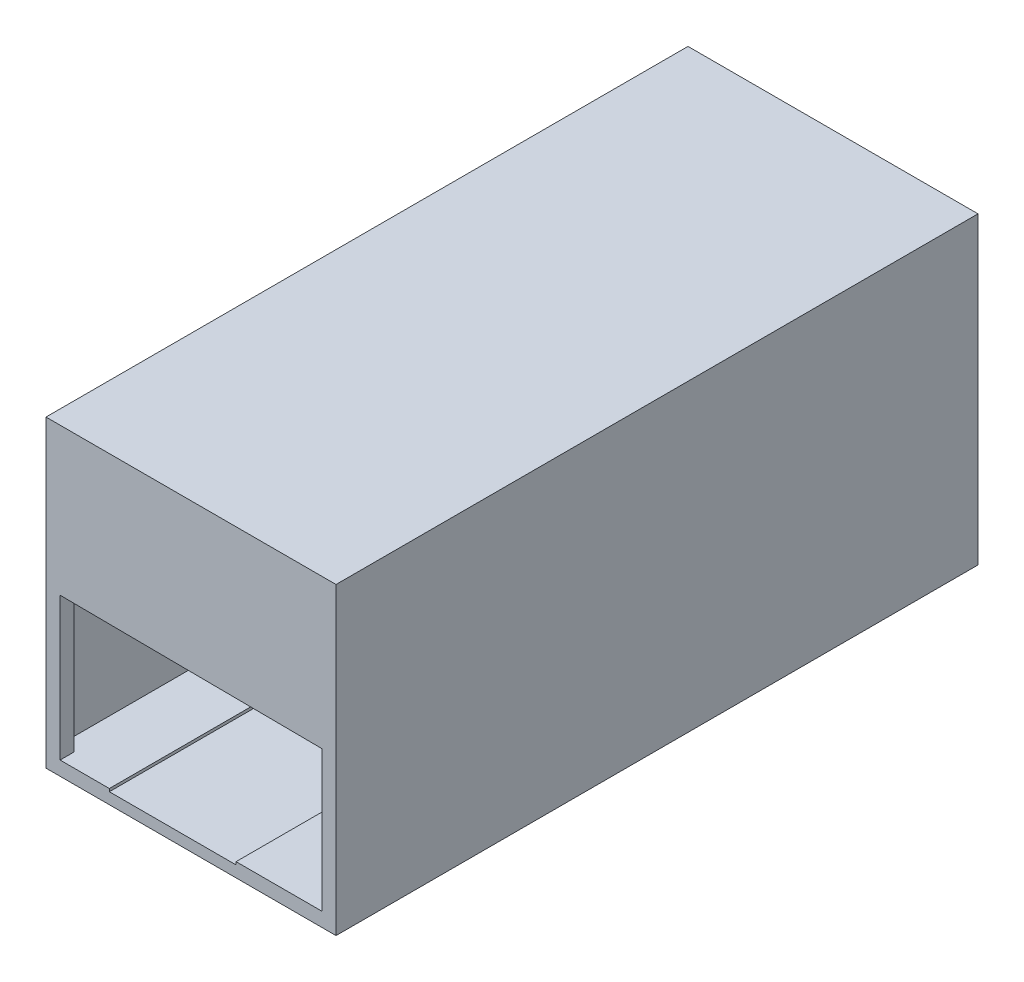
SolidWorks part; units mm, degrees
ref_plane "前视基准面" through (0, 0, 0) normal (0, 0, 1) x (1, 0, 0)
ref_plane "上视基准面" through (0, 0, 0) normal (0, 1, 0) x (1, 0, 0)
ref_plane "右视基准面" through (0, 0, 0) normal (1, 0, 0) x (0, 0, -1)
sketch "草图1" plane through (0, 0, 0) normal (0, 0, 1) x (1, 0, 0)
  line L1 (-51.5, -54) -> (51.5, -54)
  line L2 (-51.5, -54) -> (-51.5, 54)
  line L3 (-51.5, 54) -> (51.5, 54)
  line L4 (51.5, -54) -> (51.5, 54)
  line L5 (-51.5, -54) -> (51.5, 54) construction
  line L6 (-51.5, 54) -> (51.5, -54) construction
  point P0 (0, 0)
  dimension "D1" = 103
  dimension "D2" = 108
extrude "凸台-拉伸1" add sketch "草图1" against normal blind 228
sketch "草图2" plane through (0, 0, 0) normal (0, 0, 1) x (1, 0, 0)
  line L5 (-51.3, -49) -> (51.3, -49)
  line L6 (51.3, -49) -> (51.3, 49)
  line L9 (-0.804, 49) -> (51.3, 49)
  line L10 (-0.804, 49) -> (-51.3, 49)
  line L11 (-51.3, 49) -> (-51.3, -49)
extrude "切除-拉伸1" cut sketch "草图2" against normal offset from surface (218 mm away) 5 from offset 5 up to face at (0, 0, -228) offset against normal yes
sketch "草图3" plane through (0, 0, 0) normal (0, 0, 1) x (1, 0, 0)
  line L0 (51.5, -54) -> (21.4, -54) construction
  line L1 (-51.5, -54) -> (51.5, -54) construction
  line L2 (21.4, -54) -> (21.4, -24.37) construction
  circle A0 centre (21.4, -24.37) radius 8
  dimension "D3" = 16
  dimension "D1" = 30.1
  dimension "D2" = 29.63
extrude "切除-拉伸2" cut sketch "草图3" against normal blind 363
sketch "草图4" plane through (-51.5, 0, 0) normal (-1, 0, 0) x (0, 0, 1)
  line L0 (-114, 54) -> (-114, 5.82) construction
  line L1 (-228, 54) -> (0, 54) construction
  circle A0 centre (-114, 5.82) radius 23.5
  dimension "D2" = 47
  dimension "D1" = 48.18
extrude "切除-拉伸3" cut sketch "草图4" against normal up to next
sketch "草图8" plane through (0, 0, 0) normal (0, 0, 1) x (1, 0, 0)
  line L2 (0, -49) -> (46.5, -49)
  line L3 (-46.5, 1.7085) -> (-46.5, -49)
  line L7 (46.5, -49) -> (46.5, 1)
  line L8 (-46.5, -49) -> (0, -49)
  line L9 (-46.5, 1.7085) -> (46.5, 1)
  dimension "D4" = 50
extrude "切除-拉伸5" cut sketch "草图8" against normal blind 444
sketch "草图9" plane through (0, -49, 0) normal (0, 1, 0) x (1, 0, 0)
  line L1 (51.5, 0) -> (-51.5, 0) construction
  line L10 (51.5, 228) -> (-51.5, 228) construction
  line L11 (-29, 228) -> (11, 228)
  line L13 (11, 228) -> (16, 228)
  line L14 (16, 228) -> (16, 0)
  line L16 (16, 0) -> (-29, 0)
  line L17 (-29, 0) -> (-29, 228)
  dimension "D1" = 45
extrude "切除-拉伸6" cut sketch "草图9" against normal blind 1
